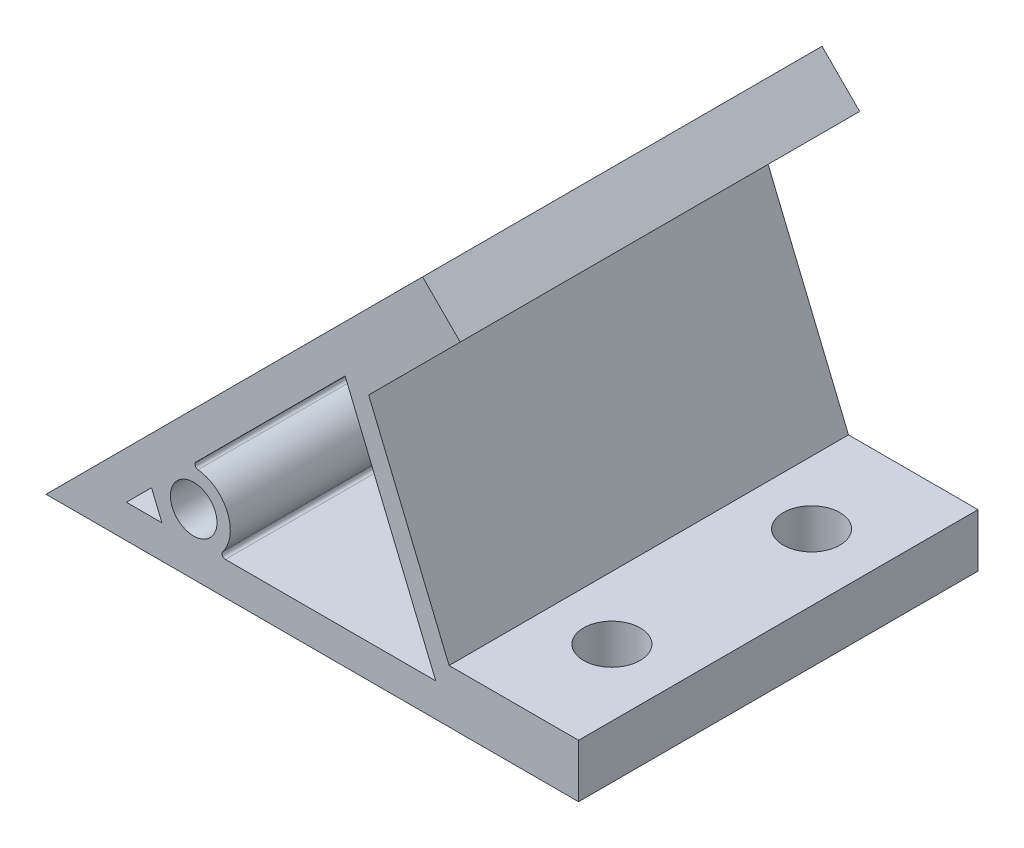
SolidWorks part; units mm, degrees
ref_plane "前视基准面" through (0, 0, 0) normal (0, 0, 1) x (1, 0, 0)
ref_plane "上视基准面" through (0, 0, 0) normal (0, 1, 0) x (1, 0, 0)
ref_plane "右视基准面" through (0, 0, 0) normal (1, 0, 0) x (0, 0, -1)
sketch "草图1" plane through (0, 0, 0) normal (0, 0, 1) x (1, 0, 0)
  line L0 (0, 0) -> (56.5685, 56.5685)
  line L1 (0, 0) -> (80, 0)
  line L2 (12.0711, 5) -> (15.8477, 8.7766)
  line L3 (12.0711, 5) -> (17.412, 5)
  line L4 (15.8477, 8.7766) -> (17.412, 5)
  line L5 (0, 0) -> (16.6385, 6.8674) construction
  line L6 (22.5392, 15.4681) -> (44.9316, 37.8605)
  line L7 (26.9418, 5) -> (58.5429, 5)
  line L8 (12.0711, 5) -> (60.1041, 53.033) construction
  line L9 (58.5429, 5) -> (44.9316, 37.8605)
  line L10 (12.0711, 5) -> (80, 5) construction
  line L11 (60.5474, 8) -> (48.4704, 37.1566)
  line L12 (61.3145, 6.1481) -> (47.7033, 39.0086) construction
  line L13 (62.2254, 50.9117) -> (56.5685, 56.5685)
  line L14 (80, 0) -> (80, 8)
  line L15 (60.5474, 8) -> (80, 8)
  line L16 (50.7665, 39.4527) -> (62.2254, 50.9117) construction
  line L17 (48.4704, 37.1566) -> (62.2254, 50.9117)
  line L18 (63.7946, 8) -> (50.7665, 39.4527) construction
  line L19 (63.7946, 8) -> (80, 8) construction
  line L20 (61.7901, 5) -> (80, 5) construction
  line L21 (47.2277, 40.1566) -> (60.1041, 53.033) construction
  line L23 (61.7901, 5) -> (47.2277, 40.1566) construction
  circle A0 centre (22.1847, 9.1565) radius 3.5
  arc A1 (26.5454, 5.8047) -> (22.8337, 14.618) centre (22.1847, 9.1565) ccw
  arc A2 (26.9418, 5) -> (26.5454, 5.8047) centre (26.9418, 5.5) cw
  circle A3 centre (22.1847, 9.1565) radius 5.5 construction
  arc A4 (22.5392, 15.4681) -> (22.8337, 14.618) centre (22.8927, 15.1145) ccw
  point P15 (27.6847, 9.1565)
  point P20 (25.7866, 5)
  point P23 (21.7067, 14.6357)
  dimension "D7" = 7
  dimension "D8" = 2
  dimension "D9" = 0.5
  dimension "D10" = 56
  dimension "D1" = 45
  dimension "D2" = 80
  dimension "D4" = 67.5
  dimension "D5" = 18
  dimension "D6" = 6
  dimension "D3" = 5
  dimension "D11" = 3
  dimension "D12" = 3
extrude "凸台-拉伸1" add sketch "草图1" along normal mid plane 60
sketch "草图2" plane through (0, 0, 0) normal (-0.7071, 0.7071, 0) x (0, 0, 1)
  line L0 (0, 80) -> (0, 53.9096) construction
  line L1 (30, 80) -> (-30, 80) construction
  circle A0 centre (-15, 70) radius 4.25
  circle A1 centre (15, 70) radius 4.25
  dimension "D1" = 30
  dimension "D3" = 8.5
  dimension "D2" = 10
extrude "切除-拉伸1" cut sketch "草图2" against normal blind 20
sketch "草图3" plane through (0, 0, 0) normal (0, -1, 0) x (1, 0, 0)
  line L0 (80, 0) -> (48.7562, 0) construction
  line L1 (80, 30) -> (80, -30) construction
  circle A0 centre (70, 15) radius 4.25
  circle A1 centre (70, -15) radius 4.25
  dimension "D1" = 30
  dimension "D2" = 10
  dimension "D3" = 8.5
extrude "切除-拉伸2" cut sketch "草图3" against normal blind 20
